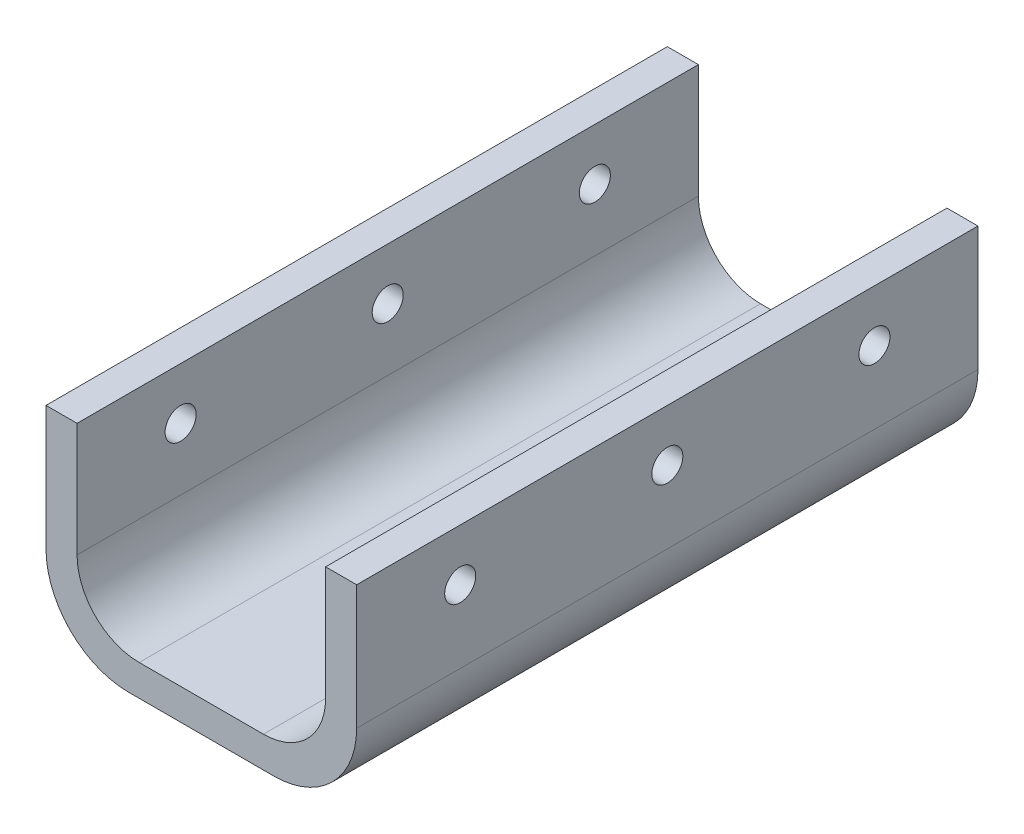
SolidWorks part; units mm, degrees
material "6061 合金"
ref_plane "前视基准面" through (0, 0, 0) normal (0, 0, 1) x (1, 0, 0)
ref_plane "上视基准面" through (0, 0, 0) normal (0, 1, 0) x (1, 0, 0)
ref_plane "右视基准面" through (0, 0, 0) normal (1, 0, 0) x (0, 0, -1)
sketch "草图1" plane through (0, 0, 0) normal (0, 0, 1) x (1, 0, 0)
  line L0 (12, -7) -> (12, 10)
  line L1 (-15, -10) -> (15, -10)
  line L2 (-15, -10) -> (-15, 10)
  line L4 (15, -10) -> (15, 10)
  line L5 (-15, -10) -> (15, 10) construction
  line L6 (-15, 10) -> (15, -10) construction
  line L7 (-12, -7) -> (12, -7)
  line L8 (-12, -7) -> (-12, 10)
  line L9 (-12, 10) -> (-15, 10)
  line L10 (12, 10) -> (15, 10)
  point P0 (0, 0)
  dimension "D1" = 20
  dimension "D2" = 30
  dimension "D3" = 3
extrude "凸台-拉伸1" add sketch "草图1" along normal blind 200
fillet "圆角1" radius 8 2 edges at (15, -10, 100) (-15, -10, 100)
fillet "圆角2" radius 6 2 edges at (12, -7, 100) (-12, -7, 100)
sketch "草图2" plane through (-15, 0, 0) normal (-1, 0, 0) x (0, 0, 1)
  line L0 (100, 10) -> (100, -2) construction
  line L1 (200, 10) -> (0, 10) construction
  line L2 (0, -2) -> (200, -2) construction
  circle A0 centre (90, 5) radius 1.5
  circle A1 centre (70, 5) radius 1.5
  circle A2 centre (50, 5) radius 1.5
  circle A3 centre (30, 5) radius 1.5
  circle A4 centre (10, 5) radius 1.5
  circle A5 centre (190, 5) radius 1.5
  circle A6 centre (170, 5) radius 1.5
  circle A7 centre (150, 5) radius 1.5
  circle A8 centre (130, 5) radius 1.5
  circle A9 centre (110, 5) radius 1.5
  dimension "D1" = 3
  dimension "D2" = 5
  dimension "D3" = 10
  dimension "D4" = 5
extrude "切除-拉伸1" cut sketch "草图2" against normal through all
sketch "草图3" plane through (-15, 0, 0) normal (-1, 0, 0) x (0, 0, 1)
  line L0 (130, 5) -> (150, 5) construction
  line L1 (140, 5) -> (140, 10) construction
  line L2 (200, 10) -> (0, 10) construction
  line L4 (140, 10) -> (203.129, 10)
  line L5 (140, 10) -> (140, -14.3167)
  line L6 (140, -14.3167) -> (203.129, -14.3167)
  line L7 (203.129, 10) -> (203.129, -14.3167)
extrude "切除-拉伸2" cut sketch "草图3" against normal blind 59
sketch "草图4" plane through (0, 0, 0) normal (0, 0, -1) x (-1, 0, 0)
  line L8 (-15, 10) -> (-15, -2)
  line L9 (-7, -10) -> (7, -10)
  line L10 (15, -2) -> (15, 10)
  line L11 (15, 10) -> (12, 10)
  line L12 (12, 10) -> (12, -1)
  line L13 (6, -7) -> (-6, -7)
  line L14 (-12, -1) -> (-12, 10)
  line L15 (-12, 10) -> (-15, 10)
  line L16 (-15, 10) -> (-15, -2)
  line L17 (-7, -10) -> (7, -10)
  line L18 (15, -2) -> (15, 10)
  line L19 (15, 10) -> (12, 10)
  line L20 (12, 10) -> (12, -1)
  line L21 (6, -7) -> (-6, -7)
  line L22 (-12, -1) -> (-12, 10)
  line L23 (-12, 10) -> (-15, 10)
  arc A4 (-15, -2) -> (-7, -10) centre (-7, -2) ccw
  arc A5 (7, -10) -> (15, -2) centre (7, -2) ccw
  arc A6 (6, -7) -> (12, -1) centre (6, -1) ccw
  arc A7 (-12, -1) -> (-6, -7) centre (-6, -1) ccw
  arc A8 (-15, -2) -> (-7, -10) centre (-7, -2) ccw
  arc A9 (7, -10) -> (15, -2) centre (7, -2) ccw
  arc A10 (6, -7) -> (12, -1) centre (6, -1) ccw
  arc A11 (-12, -1) -> (-6, -7) centre (-6, -1) ccw
  dimension "D1" = 0
extrude "切除-拉伸3" cut sketch "草图4" against normal blind 40
sketch "草图5" plane through (0, 0, 140) normal (0, 0, 1) x (1, 0, 0)
  line L8 (15, 10) -> (12, 10)
  line L9 (12, 10) -> (12, -1)
  line L10 (6, -7) -> (-6, -7)
  line L11 (-12, -1) -> (-12, 10)
  line L12 (-12, 10) -> (-15, 10)
  line L13 (-15, 10) -> (-15, -2)
  line L14 (-7, -10) -> (7, -10)
  line L15 (15, -2) -> (15, 10)
  line L16 (15, 10) -> (12, 10)
  line L17 (12, 10) -> (12, -1)
  line L18 (6, -7) -> (-6, -7)
  line L19 (-12, -1) -> (-12, 10)
  line L20 (-12, 10) -> (-15, 10)
  line L21 (-15, 10) -> (-15, -2)
  line L22 (-7, -10) -> (7, -10)
  line L23 (15, -2) -> (15, 10)
  arc A4 (6, -7) -> (12, -1) centre (6, -1) ccw
  arc A5 (-12, -1) -> (-6, -7) centre (-6, -1) ccw
  arc A6 (-15, -2) -> (-7, -10) centre (-7, -2) ccw
  arc A7 (7, -10) -> (15, -2) centre (7, -2) ccw
  arc A8 (6, -7) -> (12, -1) centre (6, -1) ccw
  arc A9 (-12, -1) -> (-6, -7) centre (-6, -1) ccw
  arc A10 (-15, -2) -> (-7, -10) centre (-7, -2) ccw
  arc A11 (7, -10) -> (15, -2) centre (7, -2) ccw
  dimension "D1" = 0
extrude "切除-拉伸4" cut sketch "草图5" against normal blind 40
